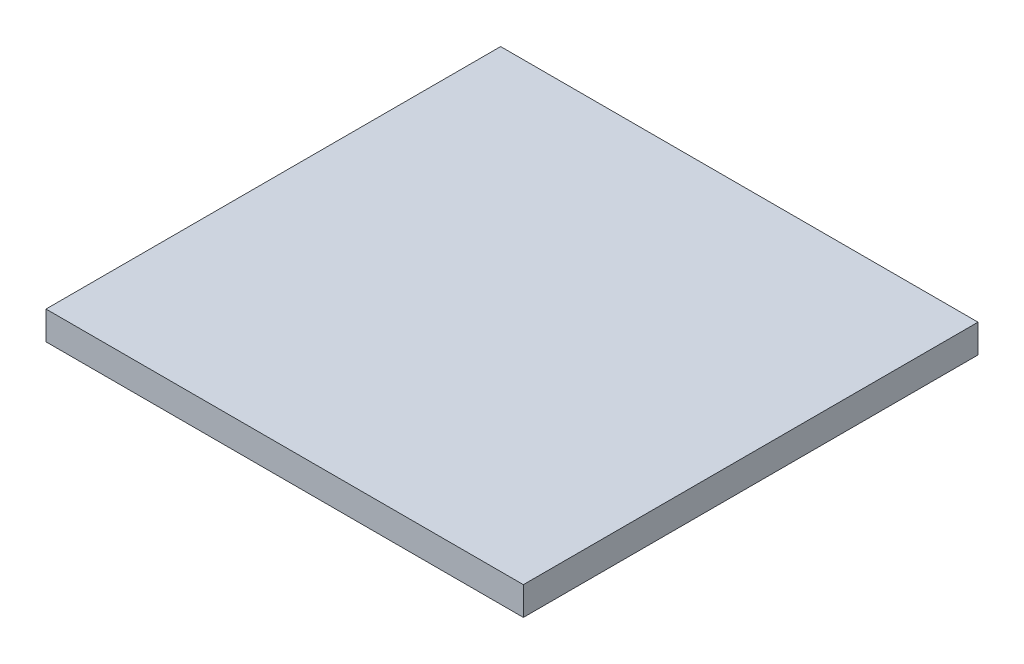
SolidWorks part; units mm, degrees
material "PMMA"
ref_plane "Front Plane" through (0, 0, 0) normal (0, 0, 1) x (1, 0, 0)
ref_plane "Top Plane" through (0, 0, 0) normal (0, 1, 0) x (1, 0, 0)
ref_plane "Right Plane" through (0, 0, 0) normal (1, 0, 0) x (0, 0, -1)
sketch "Sketch1" plane through (0, 0, 0) normal (0, 1, 0) x (1, 0, 0)
  line L1 (0, 0) -> (53.34, 0)
  line L2 (0, 0) -> (0, 50.8)
  line L3 (0, 50.8) -> (53.34, 50.8)
  line L4 (53.34, 0) -> (53.34, 50.8)
  dimension "D1" = 50.8
  dimension "D2" = 53.34
extrude "Boss-Extrude1" add sketch "Sketch1" along normal blind 3.175
equation "\"PLEX_THICKNESS\"= 1 / 8"
equation "\"D1@Boss-Extrude1\"=\"PLEX_THICKNESS\""
